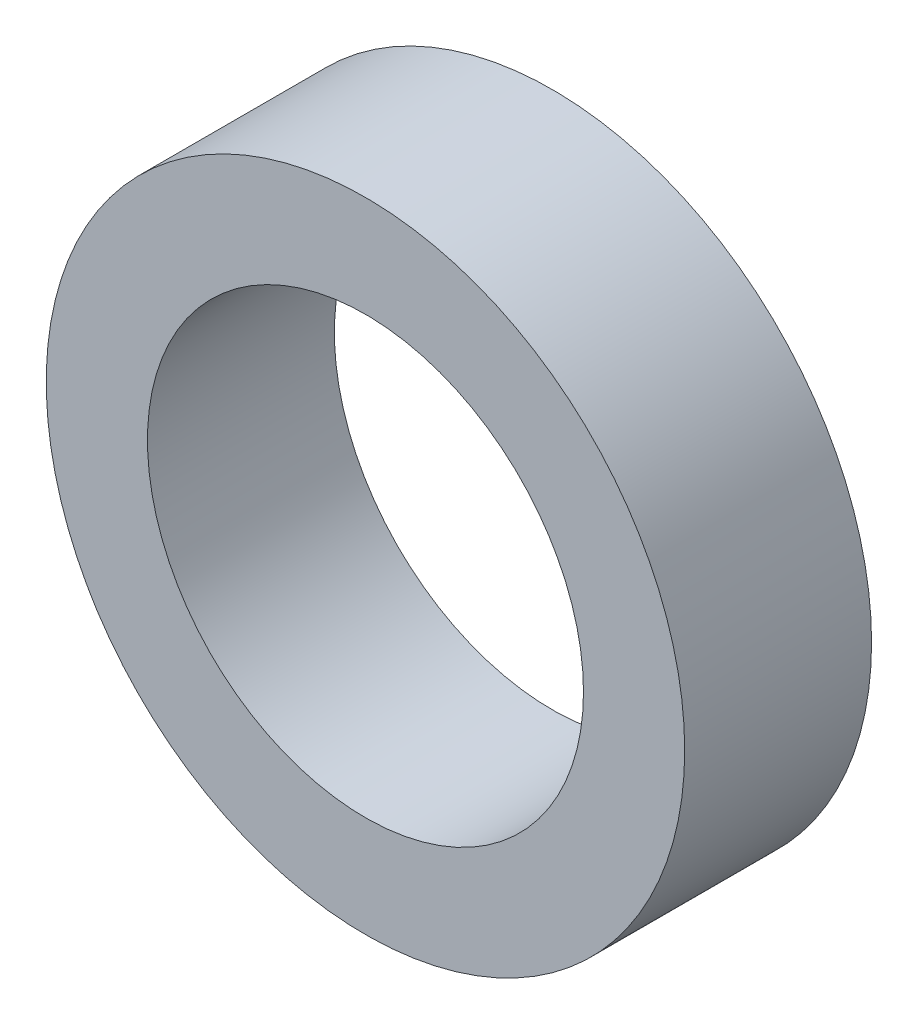
SolidWorks part; units mm, degrees
ref_plane "Front Plane" through (0, 0, 0) normal (0, 0, 1) x (1, 0, 0)
ref_plane "Top Plane" through (0, 0, 0) normal (0, 1, 0) x (1, 0, 0)
ref_plane "Right Plane" through (0, 0, 0) normal (1, 0, 0) x (0, 0, -1)
sketch "Sketch1" plane through (0, 0, 0) normal (0, 0, 1) x (1, 0, 0)
  circle A0 centre (0, 0) radius 20.5
  circle A1 centre (0, 0) radius 14
  dimension "D1" = 28
  dimension "D2" = 41
extrude "Boss-Extrude1" add sketch "Sketch1" against normal blind 12
